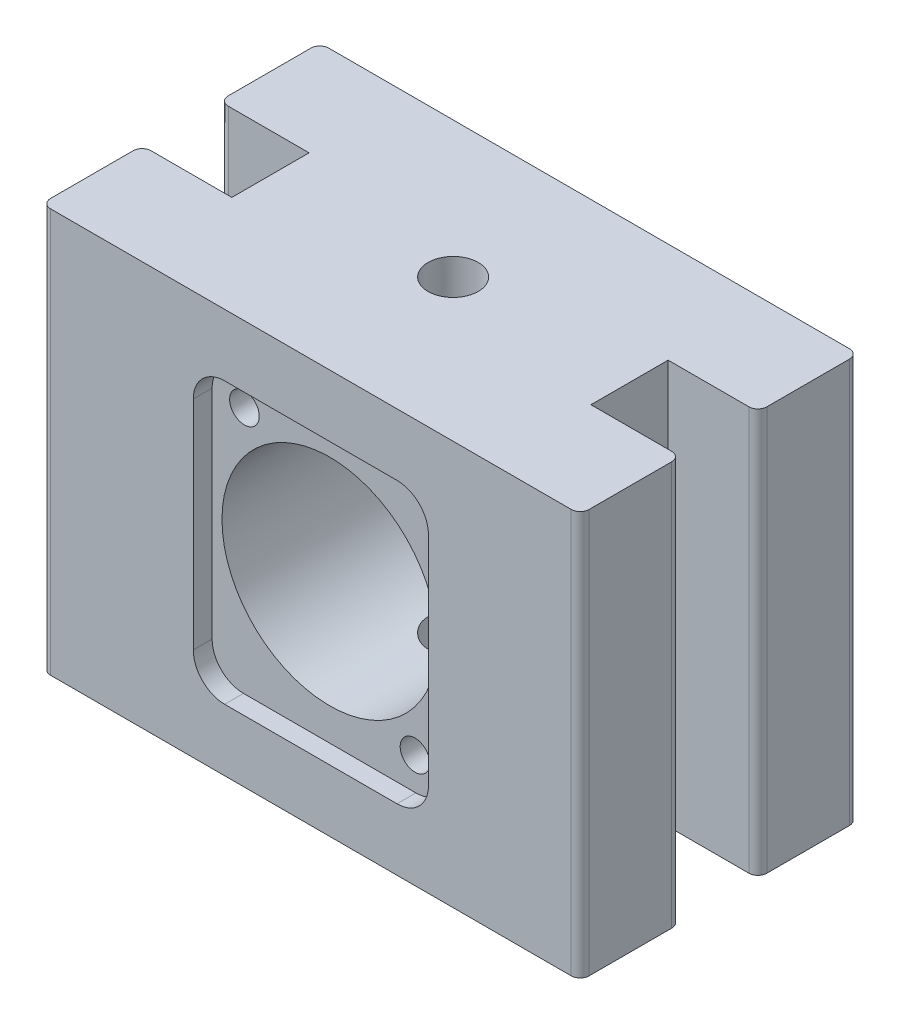
SolidWorks part; units mm, degrees
ref_plane "Front Plane" through (0, 0, 0) normal (0, 0, 1) x (1, 0, 0)
ref_plane "Top Plane" through (0, 0, 0) normal (0, 1, 0) x (1, 0, 0)
ref_plane "Right Plane" through (0, 0, 0) normal (1, 0, 0) x (0, 0, -1)
sketch "Sketch1" plane through (0, 0, 0) normal (0, 1, 0) x (1, 0, 0)
  line L0 (20, 3.95) -> (29, 3.95)
  line L1 (-20, 15.15) -> (13.4494, 15.15)
  line L2 (-20, 3.95) -> (-20, -4.65)
  line L3 (-20, -15.85) -> (20, -15.85)
  line L4 (20, 3.95) -> (20, -4.65)
  line L7 (-29, 15.15) -> (29, 15.15)
  line L8 (-30, 14.15) -> (-30, 4.95)
  line L9 (-29, 3.95) -> (-20, 3.95)
  line L10 (30, 14.15) -> (30, 4.95)
  line L11 (-29, -15.85) -> (29, -15.85)
  line L12 (-30, -14.85) -> (-30, -5.65)
  line L13 (-29, -4.65) -> (-20, -4.65)
  line L14 (30, -14.85) -> (30, -5.65)
  line L15 (20, -4.65) -> (29, -4.65)
  arc A0 (-29, -15.85) -> (-30, -14.85) centre (-29, -14.85) cw
  arc A1 (-30, -5.65) -> (-29, -4.65) centre (-29, -5.65) cw
  arc A2 (-30, 4.95) -> (-29, 3.95) centre (-29, 4.95) ccw
  arc A3 (-29, 15.15) -> (-30, 14.15) centre (-29, 14.15) ccw
  arc A4 (29, -15.85) -> (30, -14.85) centre (29, -14.85) ccw
  arc A5 (29, -4.65) -> (30, -5.65) centre (29, -5.65) cw
  arc A6 (29, 3.95) -> (30, 4.95) centre (29, 4.95) ccw
  arc A7 (29, 15.15) -> (30, 14.15) centre (29, 14.15) cw
  circle A8 centre (0, 0) radius 2.8
  point P0 (0, 0)
  dimension "D6" = 1
  dimension "D7" = 1
  dimension "D8" = 5.6
  dimension "D1" = 40
  dimension "D2" = 31
  dimension "D3" = 8.6
  dimension "D4" = 10
  dimension "D5" = 10
extrude "Boss-Extrude1" add sketch "Sketch1" along normal blind 45 contours A7 L7 L1 A3 L8 A2 L9 L2 L13 A1 L12 A0 L11 L3 A4 L14 A5 L15 L4 L0 A6 L10 A8
sketch "Sketch2" plane through (0, 0, 15.85) normal (0, 0, 1) x (1, 0, 0)
  line L0 (-29, 45) -> (-29, 0) construction
  circle A0 centre (0, 22.5) radius 12
  circle A1 centre (-9.5, 34.5) radius 1.65
  circle A2 centre (9.5, 10.5) radius 1.65
  point P6 (-29, 22.5)
  dimension "D1" = 24
  dimension "D2" = 3.3
  dimension "D3" = 3.3
  dimension "D4" = 19
  dimension "D5" = 24
  dimension "D6" = 9.5
  dimension "D7" = 12
extrude "Cut-Extrude1" cut sketch "Sketch2" against normal blind 56
sketch "Sketch3" plane through (0, 0, 15.85) normal (0, 0, 1) x (1, 0, 0)
  line L1 (-9.6, 38.1) -> (9.6, 38.1)
  line L2 (-13.1, 34.6) -> (-13.1, 10.4)
  line L3 (-9.6, 6.9) -> (9.6, 6.9)
  line L4 (13.1, 34.6) -> (13.1, 10.4)
  line L5 (-13.1, 38.1) -> (13.1, 6.9) construction
  line L6 (-13.1, 6.9) -> (13.1, 38.1) construction
  arc A0 (9.6, 6.9) -> (13.1, 10.4) centre (9.6, 10.4) ccw
  arc A1 (-13.1, 10.4) -> (-9.6, 6.9) centre (-9.6, 10.4) ccw
  arc A2 (9.6, 38.1) -> (13.1, 34.6) centre (9.6, 34.6) cw
  arc A3 (-9.6, 38.1) -> (-13.1, 34.6) centre (-9.6, 34.6) ccw
  point P0 (0, 22.5)
  dimension "D3" = 3.5
  dimension "D1" = 31.2
  dimension "D2" = 26.2
extrude "Cut-Extrude2" cut sketch "Sketch3" against normal blind 2.1 from surface at 0 starting at face at (11.15, 10.5, 15.85)
